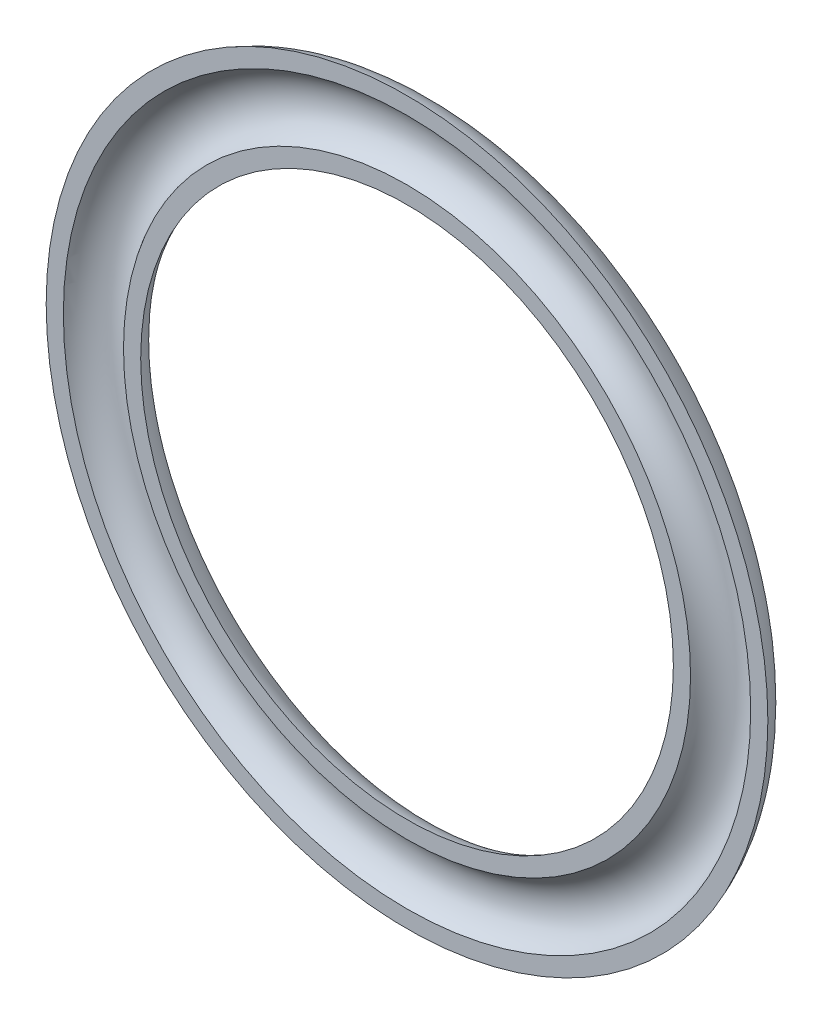
SolidWorks part; units mm, degrees
ref_plane "前视基准面" through (0, 0, 0) normal (0, 0, 1) x (1, 0, 0)
ref_plane "上视基准面" through (0, 0, 0) normal (0, 1, 0) x (1, 0, 0)
ref_plane "右视基准面" through (0, 0, 0) normal (1, 0, 0) x (0, 0, -1)
other "Configuration Table"
sketch "草图1" plane through (0, 0, 0) normal (0, 0, 1) x (1, 0, 0)
  circle A0 centre (0, 0) radius 15.5
  circle A1 centre (0, 0) radius 21
extrude "凸台-拉伸1" add sketch "草图1" along normal blind 2
sketch "草图2" plane through (0, 0, 0) normal (0, 1, 0) x (1, 0, 0)
  line L0 (0, 0) -> (-16.5, 0) construction
  line L1 (21, 0) -> (-21, 0) construction
  line L4 (0, 0) -> (0, 4.7874) construction
  line L5 (-21, 0) -> (-20, 0)
  line L6 (-16.5, 0) -> (-15.5, 0)
  line L8 (-20, 0) -> (-21, 0) construction
  arc A0 (-21, 0) -> (-15.5, 0) centre (-18.25, -0.8596) cw
  arc A1 (-16.5, 0) -> (-20, 0) centre (-18.25, -0.8596) ccw
revolve "旋转1" add sketch "草图2" angle 360 about L4
sketch "草图3" plane through (0, 0, 2) normal (0, 0, 1) x (1, 0, 0)
  circle A0 centre (0, 0) radius 21
extrude "切除-拉伸1" cut sketch "草图3" against normal blind 2
